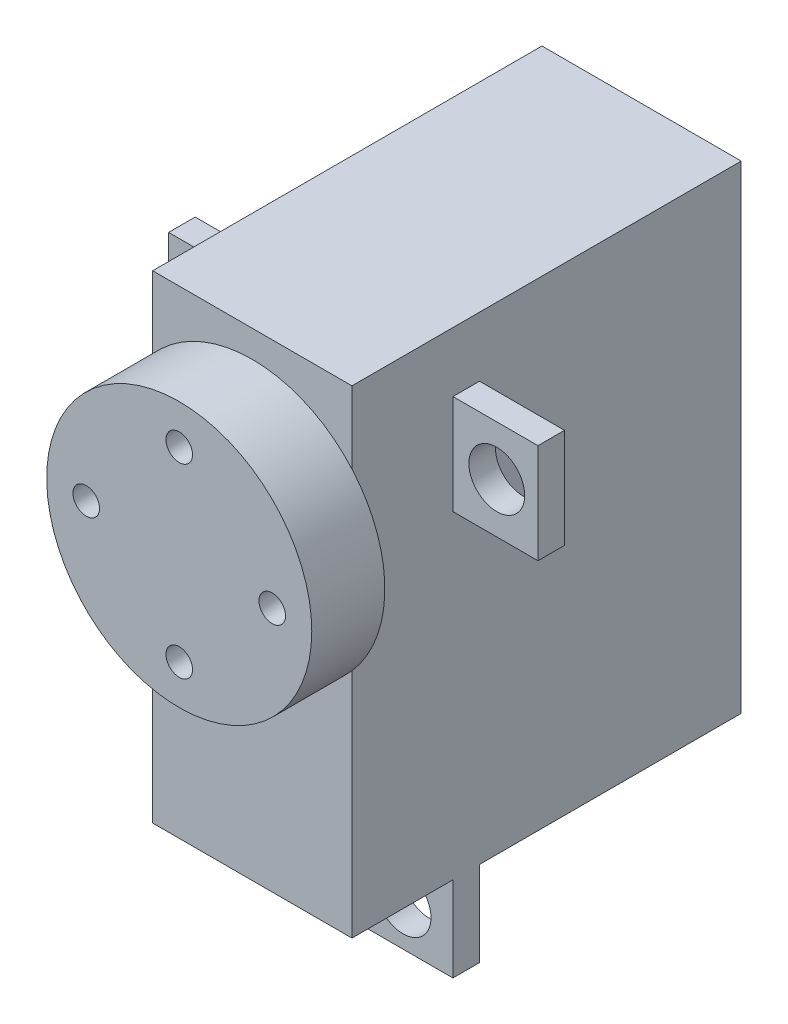
SolidWorks part; units mm, degrees
ref_plane "정면" through (0, 0, 0) normal (0, 0, 1) x (1, 0, 0)
ref_plane "윗면" through (0, 0, 0) normal (0, 1, 0) x (1, 0, 0)
ref_plane "우측면" through (0, 0, 0) normal (1, 0, 0) x (0, 0, -1)
sketch "스케치1" plane through (0, 0, 0) normal (0, 0, 1) x (1, 0, 0)
  line L1 (-7.5, 18) -> (7.5, 18)
  line L2 (-7.5, 18) -> (-7.5, -18)
  line L3 (-7.5, -18) -> (7.5, -18)
  line L4 (7.5, 18) -> (7.5, -18)
  line L5 (-7.5, 18) -> (7.5, -18) construction
  line L6 (-7.5, -18) -> (7.5, 18) construction
  point P0 (0, 0)
  dimension "D1" = 15
  dimension "D2" = 36
extrude "보스-돌출1" add sketch "스케치1" along normal blind 29.3
sketch "스케치2" plane through (0, 0, 29.3) normal (0, 0, 1) x (1, 0, 0)
  line L0 (-7.5, 18) -> (-7.5, -18) construction
  circle A0 centre (0, 6) radius 9.975
  circle A1 centre (0, 6) radius 7 construction
  circle A2 centre (0, 13) radius 1
  circle A3 centre (7, 6) radius 1
  circle A4 centre (0, -1) radius 1
  circle A5 centre (-7, 6) radius 1
  point P4 (-7.5, 0)
  dimension "D1" = 19.95
  dimension "D2" = 6
  dimension "D3" = 14
  dimension "D4" = 2
extrude "보스-돌출2" add sketch "스케치2" along normal blind 5.5
sketch "스케치3" plane through (0, 0, 0) normal (0, 0, -1) x (-1, 0, 0)
  line L0 (-7.5, -18) -> (-7.5, 18) construction
  line L1 (-7.5, -18) -> (7.5, -18)
  line L2 (-7.5, -18) -> (-7.5, -24.4)
  line L3 (-7.5, -24.4) -> (7.5, -24.4)
  line L4 (7.5, -18) -> (7.5, -24.4)
  line L5 (-7.5, 13.5) -> (-13.9, 13.5)
  line L6 (-7.5, 13.5) -> (-7.5, 6)
  line L7 (-7.5, 6) -> (-13.9, 6)
  line L8 (-13.9, 13.5) -> (-13.9, 6)
  line L9 (7.5, 18) -> (7.5, -18) construction
  line L10 (7.5, 13.5) -> (13.9, 13.5)
  line L11 (7.5, 13.5) -> (7.5, 6)
  line L12 (7.5, 6) -> (13.9, 6)
  line L13 (13.9, 13.5) -> (13.9, 6)
  line L14 (-7.5, 18) -> (7.5, 18) construction
  line L15 (-3.75, -21.3) -> (3.75, -21.3) construction
  line L16 (-10.8, 9.75) -> (10.8, 9.75) construction
  circle A0 centre (-10.8, 9.75) radius 2.1
  circle A1 centre (10.8, 9.75) radius 2.1
  circle A2 centre (-3.75, -21.3) radius 2.1
  circle A3 centre (3.75, -21.3) radius 2.1
  point P23 (0, -24.4)
  point P24 (0, 9.75)
  dimension "D11" = 4.2
  dimension "D1" = 6.4
  dimension "D2" = 7.5
  dimension "D3" = 12
  dimension "D4" = 6.4
  dimension "D5" = 21.3
  dimension "D6" = 7.5
  dimension "D7" = 3.75
  dimension "D8" = 3.3
  dimension "D9" = 3.3
  dimension "D10" = 3.75
extrude "보스-돌출3" add sketch "스케치3" against normal blind 2 from offset 19.7 offset against normal yes
sketch "스케치4" plane through (0, -18, 0) normal (0, -1, 0) x (1, 0, 0)
  line L0 (-7.5, 0) -> (7.5, 0) construction
  line L1 (-3, 0) -> (3, 0)
  line L2 (-3, 0) -> (-3, 5)
  line L3 (-3, 5) -> (3, 5)
  line L4 (3, 0) -> (3, 5)
  line L5 (7.5, 19.7) -> (7.5, 0) construction
  dimension "D1" = 5
  dimension "D2" = 6
  dimension "D3" = 4.5
extrude "보스-돌출4" add sketch "스케치4" along normal blind 4
